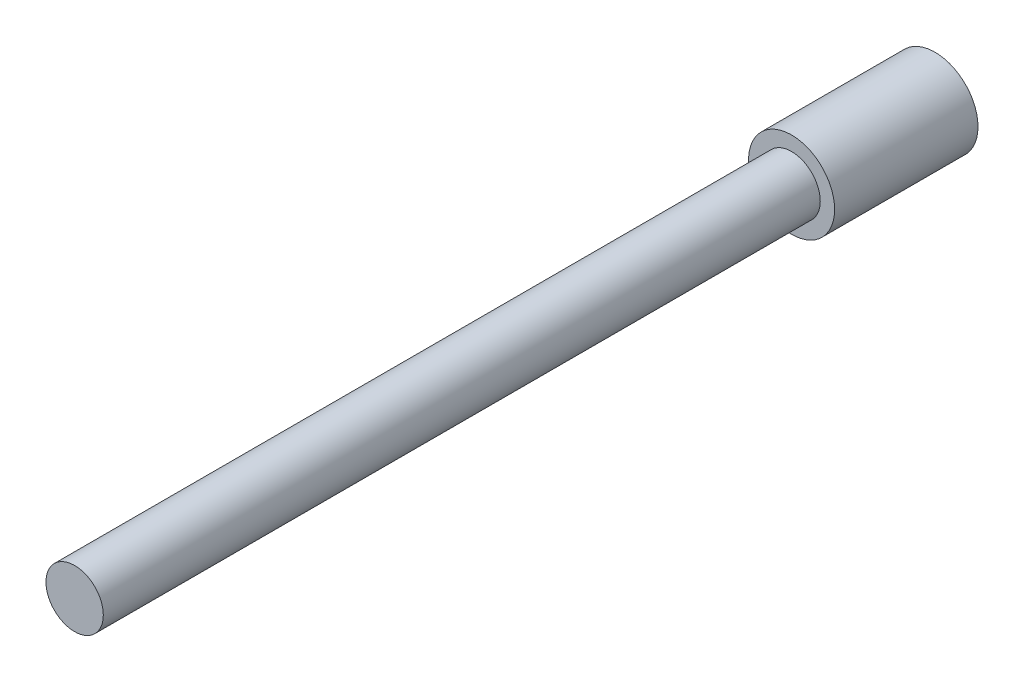
SolidWorks part; units mm, degrees
material "Stainless Steel (ferritic)"
ref_plane "Front Plane" through (0, 0, 0) normal (0, 0, 1) x (1, 0, 0)
ref_plane "Top Plane" through (0, 0, 0) normal (0, 1, 0) x (1, 0, 0)
ref_plane "Right Plane" through (0, 0, 0) normal (1, 0, 0) x (0, 0, -1)
sketch "Sketch1" plane through (0, 0, 0) normal (0, 1, 0) x (1, 0, 0)
  line L0 (6, 20) -> (0, 20)
  line L1 (0, 20) -> (0, -100)
  line L2 (0, -100) -> (4, -100)
  line L3 (4, -100) -> (4, 0)
  line L4 (4, 0) -> (6, 0)
  line L5 (6, 0) -> (6, 20)
  line L6 (0, 20) -> (0, -100) construction
revolve "Revolve1" add sketch "Sketch1" angle 360 about L6
